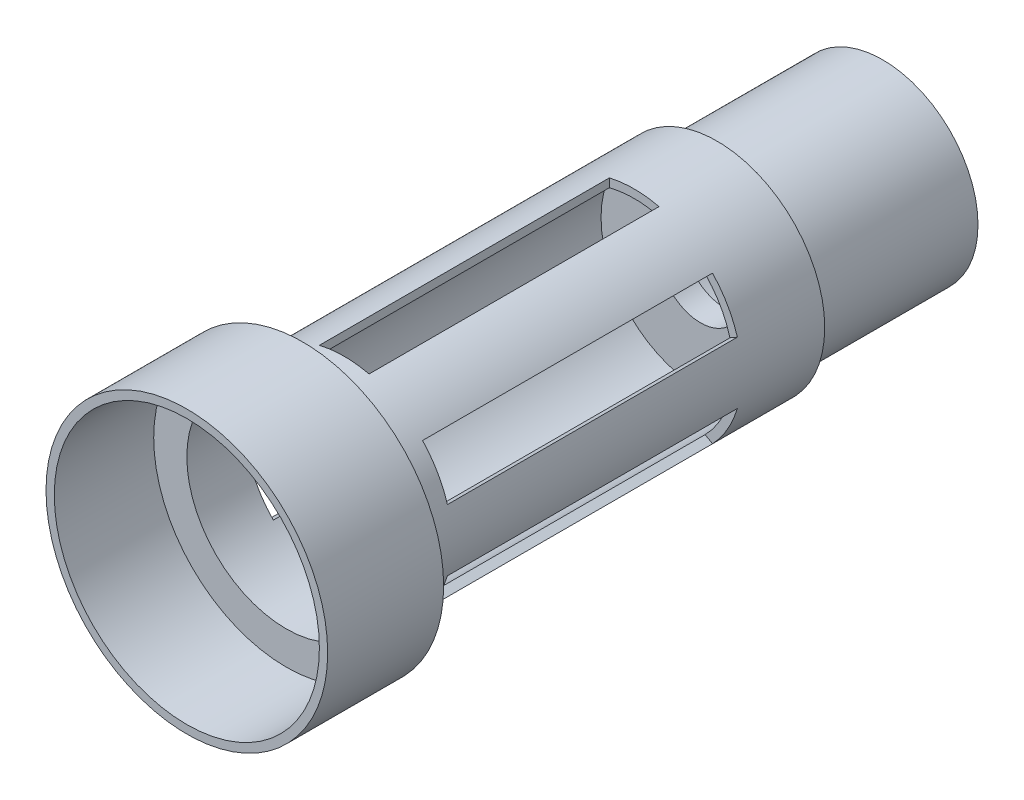
SolidWorks part; units mm, degrees
ref_plane "Front Plane" through (0, 0, 0) normal (0, 0, 1) x (1, 0, 0)
ref_plane "Top Plane" through (0, 0, 0) normal (0, 1, 0) x (1, 0, 0)
ref_plane "Right Plane" through (0, 0, 0) normal (1, 0, 0) x (0, 0, -1)
sketch "Sketch1" plane through (0, 0, 0) normal (0, 0, 1) x (1, 0, 0)
  circle A0 centre (0, 0) radius 14.605
  dimension "D1" = 29.21
extrude "Boss-Extrude1" add sketch "Sketch1" along normal blind 25.4
sketch "Sketch2" plane through (0, 0, 25.4) normal (0, 0, 1) x (1, 0, 0)
  circle A0 centre (0, 0) radius 16.51
  dimension "D1" = 33.02
extrude "Boss-Extrude2" add sketch "Sketch2" along normal blind 63.5
sketch "Sketch5" plane through (0, 0, 0) normal (0, 0, -1) x (-1, 0, 0)
  circle A0 centre (0, 0) radius 13.462
  dimension "D1" = 26.924
extrude "Cut-Extrude1" cut sketch "Sketch5" against normal blind 24.13
sketch "Sketch6" plane through (0, 0, 88.9) normal (0, 0, 1) x (1, 0, 0)
  circle A0 centre (0, 0) radius 15.24
  dimension "D1" = 30.48
extrude "Cut-Extrude3" cut sketch "Sketch6" against normal blind 60.96
sketch "Sketch7" plane through (0, 0, 27.94) normal (0, 0, 1) x (1, 0, 0)
  circle A0 centre (0, 0) radius 6.35
  dimension "D1" = 12.7
extrude "Cut-Extrude4" cut sketch "Sketch7" against normal up to next
sketch "Sketch9" plane through (0, 0, 0) normal (0, 1, 0) x (1, 0, 0)
  line L1 (-3.81, -38.1) -> (3.81, -38.1)
  line L2 (-3.81, -38.1) -> (-3.81, -82.55)
  line L3 (-3.81, -82.55) -> (3.81, -82.55)
  line L4 (3.81, -38.1) -> (3.81, -82.55)
  point P4 (0, -38.1)
  dimension "D1" = 38.1
  dimension "D2" = 44.45
  dimension "D3" = 7.62
extrude "Cut-Extrude5" cut sketch "Sketch9" against normal through all and the other way through all
pattern_circular "CirPattern1" count 3 over 360 about axis through (0, 0, 0) along (0, 0, 1) of "Cut-Extrude5"
sketch "Sketch10" plane through (0, 0, 88.9) normal (0, 0, 1) x (1, 0, 0)
  circle A0 centre (0, 0) radius 15.24
  circle A1 centre (0, 0) radius 20.32
  circle A3 centre (0, 0) radius 15.24 construction
  dimension "D1" = 40.64
extrude "Boss-Extrude3" add sketch "Sketch10" along normal blind 2.54 separate body
sketch "Sketch11" plane through (0, 0, 91.44) normal (0, 0, 1) x (1, 0, 0)
  circle A0 centre (0, 0) radius 21.59
  circle A1 centre (0, 0) radius 20.32
  dimension "D1" = 43.18
  dimension "D2" = 40.64
extrude "Boss-Extrude4" add sketch "Sketch11" along normal blind 15.24 separate body
sketch "Sketch12" plane through (0, 0, 91.44) normal (0, 0, -1) x (-1, 0, 0)
  circle A0 centre (0, 0) radius 21.59
  circle A1 centre (0, 0) radius 20.32
  circle A2 centre (0, 0) radius 20.32 construction
  circle A3 centre (0, 0) radius 21.59 construction
extrude "Boss-Extrude5" add sketch "Sketch12" along normal blind 2.54
